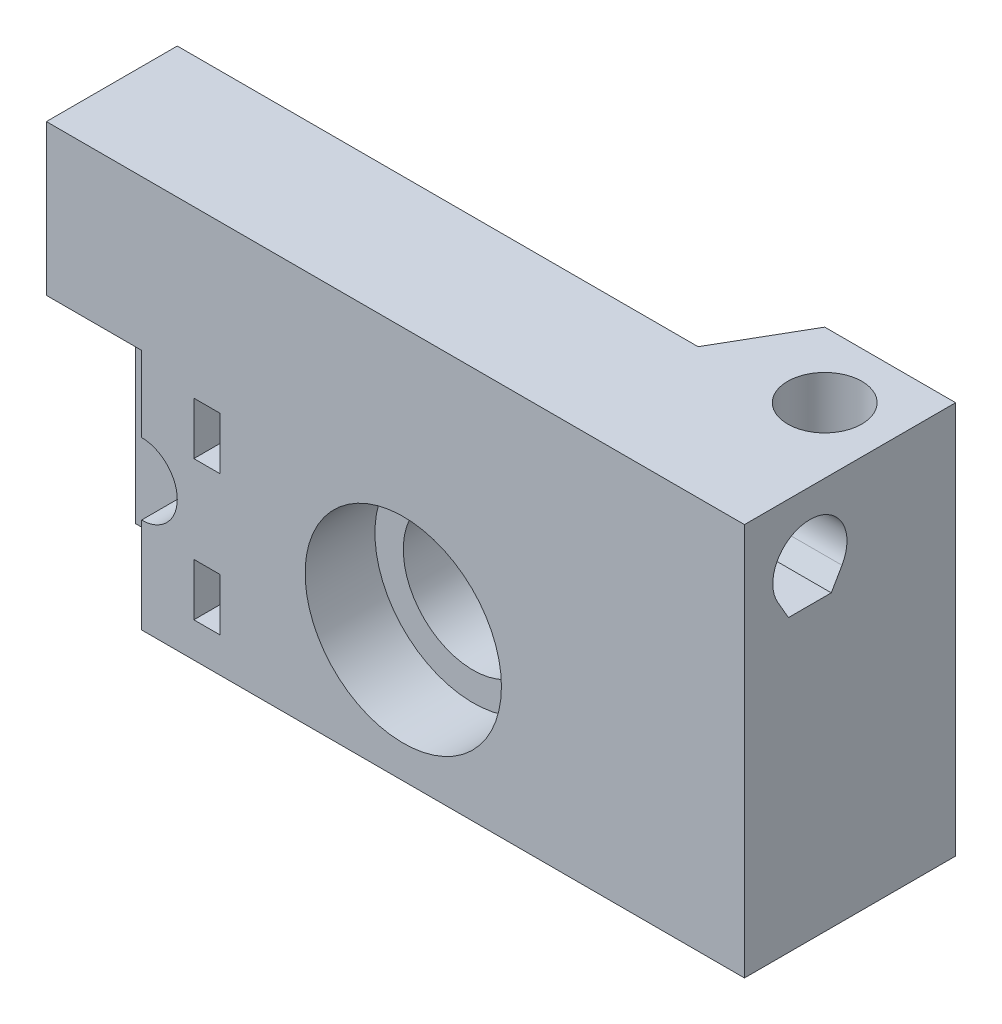
SolidWorks part; units mm, degrees
ref_plane "Piano frontale" through (0, 0, 0) normal (0, 0, 1) x (1, 0, 0)
ref_plane "Piano superiore" through (0, 0, 0) normal (0, 1, 0) x (1, 0, 0)
ref_plane "Piano destro" through (0, 0, 0) normal (1, 0, 0) x (0, 0, -1)
sketch "Schizzo2" plane through (0, 0, 0) normal (0, 0, 1) x (1, 0, 0)
  line L1 (40, -15) -> (-40, -15)
  line L2 (40, -15) -> (40, 15)
  line L3 (40, 15) -> (-40, 15)
  line L4 (-40, -15) -> (-40, 15)
  line L5 (40, -15) -> (-40, 15) construction
  line L6 (40, 15) -> (-40, -15) construction
  point P0 (0, 0)
  dimension "D1" = 30
  dimension "D2" = 80
extrude "Estrusione-Estrusione1" add sketch "Schizzo2" along normal mid plane 24.2
sketch "Schizzo3" plane through (0, -15, 0) normal (0, -1, 0) x (1, 0, 0)
  line L1 (40, 12.1) -> (40, -12.1) construction
  line L2 (-40, -12.1) -> (40, -12.1) construction
  circle A0 centre (32.5, -4.6) radius 4.25
  dimension "D2" = 8.5
  dimension "D1" = 7.5
  dimension "D3" = 7.5
extrude "Taglio-Estrusione1" cut sketch "Schizzo3" against normal through all contours A0
sketch "Schizzo4" plane through (0, 0, 12.1) normal (0, 0, 1) x (1, 0, 0)
  line L0 (0, 0) -> (0.9, 0) construction
  line L1 (28.25, -15) -> (36.75, -15) construction
  line L2 (28.25, -15) -> (36.75, -15) construction
  line L3 (32.5, -15) -> (32.5, 15) construction
  line L4 (40, 15) -> (-40, 15) construction
  circle A0 centre (0.9, 0) radius 11.25
  dimension "D1" = 22.5
  dimension "D2" = 31.6
extrude "Taglio-Estrusione2" cut sketch "Schizzo4" against normal blind 8
sketch "Schizzo5" plane through (0, 0, 4.1) normal (0, 0, 1) x (1, 0, 0)
  circle A0 centre (0.9, 0) radius 11.25 construction
  circle A1 centre (0.9, 0) radius 11.25 construction
  circle A2 centre (0.9, 0) radius 8
  dimension "D1" = 16
extrude "Taglio-Estrusione3" cut sketch "Schizzo5" against normal through all contours A2
sketch "Schizzo6" plane through (0, 15, 0) normal (0, 1, 0) x (1, 0, 0)
  line L4 (40, 12.1) -> (-40, 12.1)
  line L5 (-40, 12.1) -> (-40, -12.1)
  line L6 (-40, -12.1) -> (40, -12.1)
  line L7 (40, -12.1) -> (40, 12.1)
  line L8 (40, 12.1) -> (-40, 12.1)
  line L9 (-40, 12.1) -> (-40, -12.1)
  line L10 (-40, -12.1) -> (40, -12.1)
  line L11 (40, -12.1) -> (40, 12.1)
  circle A0 centre (32.5, 4.6) radius 4.25 construction
  circle A1 centre (32.5, 4.6) radius 4.25
  dimension "D1" = 0
extrude "Estrusione-Estrusione2" add sketch "Schizzo6" along normal blind 15
sketch "Schizzo7" plane through (40, 0, 0) normal (1, 0, 0) x (0, 0, -1)
  line L0 (-2.1463, 18.25) -> (-7.0537, 18.25)
  line L1 (-7.0537, 18.25) -> (-8.2806, 20.375)
  line L2 (-12.1, 30) -> (12.1, 30) construction
  line L3 (-2.1463, 18.25) -> (-0.9194, 20.375)
  line L4 (-12.1, -15) -> (-12.1, 30) construction
  arc A0 (-0.9194, 20.375) -> (-8.2806, 20.375) centre (-4.6, 22.5) ccw
  point P9 (-4.6, 18.25)
  dimension "D2" = 8.5
  dimension "D1" = 7.5
  dimension "D3" = 7.5
  dimension "D4" = 120
extrude "Taglio-Estrusione4" cut sketch "Schizzo7" against normal through all
sketch "Schizzo8" plane through (0, 0, 12.1) normal (0, 0, 1) x (1, 0, 0)
  line L0 (-29.1, 0) -> (0.9, 0) construction
  circle A0 centre (0.9, 0) radius 11.25 construction
  circle A1 centre (0.9, 0) radius 11.25 construction
  circle A2 centre (-29.1, 0) radius 4.1
  dimension "D2" = 8.2
  dimension "D1" = 30
sketch "Schizzo9" plane through (0, -15, 0) normal (0, -1, 0) x (1, 0, 0)
  line L0 (25, -12.1) -> (19.6884, -2.9)
  line L1 (-40, -12.1) -> (40, -12.1) construction
  line L2 (19.6884, -2.9) -> (-40, -2.9)
  line L3 (-40, 12.1) -> (-40, -12.1) construction
  line L4 (-40, -2.9) -> (-40, -12.1)
  line L5 (-40, -12.1) -> (25, -12.1)
  line L6 (-40, 12.1) -> (40, 12.1) construction
  dimension "D1" = 15
  dimension "D2" = 60
  dimension "D3" = 15
extrude "Taglio-Estrusione5" cut sketch "Schizzo9" against normal through all
extrude "Taglio-Estrusione6" cut sketch "Schizzo8" against normal blind 12 contours A2
sketch "Schizzo10" plane through (-40, 0, 0) normal (-1, 0, 0) x (0, 0, 1)
  line L0 (1.9, 12.75) -> (1.9, -15)
  line L2 (1.9, 12.75) -> (12.1, 12.75)
  line L3 (12.1, 30) -> (12.1, -15) construction
  line L5 (12.1, -4.1) -> (12.1, 4.1) construction
  line L6 (12.1, -4.1) -> (12.1, 4.1) construction
  line L7 (12.1, 0) -> (1.9, 0) construction
  line L8 (12.1, -15) -> (-2.9, -15) construction
  line L9 (1.9, -15) -> (12.1, -15)
  line L10 (12.1, -15) -> (12.1, 12.75)
  point P15 (7.1, 0)
  dimension "D1" = 10.2
  dimension "D5" = 12.75
extrude "Taglio-Estrusione7" cut sketch "Schizzo10" against normal blind 10.9 contours L0 L9 L10 L2
sketch "Schizzo11" plane through (-29.1, 0, 0) normal (-1, 0, 0) x (0, 0, 1)
  line L0 (12.1, -4.1) -> (12.1, 4.1) construction
  line L1 (12.1, -4.1) -> (12.1, 4.1) construction
  line L2 (12.1, 0) -> (7.1, 0) construction
  line L3 (7.1, -8) -> (7.1, 8) construction
  line L4 (8.1104, 6.25) -> (6.0896, 6.25)
  line L5 (8.1104, -9.75) -> (6.0896, -9.75)
  line L6 (8.1104, -9.75) -> (8.6155, -8.875)
  line L7 (6.0896, -9.75) -> (5.5845, -8.875)
  line L8 (8.1104, 6.25) -> (8.6155, 7.125)
  line L9 (6.0896, 6.25) -> (5.5845, 7.125)
  arc A0 (8.6155, 7.125) -> (5.5845, 7.125) centre (7.1, 8) ccw
  arc A1 (8.6155, -8.875) -> (5.5845, -8.875) centre (7.1, -8) ccw
  point P8 (7.1, 0)
  point P13 (7.1, 6.25)
  point P16 (7.1, -9.75)
  dimension "D3" = 3.5
  dimension "D1" = 5
  dimension "D2" = 8
  dimension "D4" = 120
  dimension "D5" = 120
extrude "Taglio-Estrusione8" cut sketch "Schizzo11" against normal blind 12
sketch "Schizzo12" plane through (0, 0, 12.1) normal (0, 0, 1) x (1, 0, 0)
  line L0 (-21.6, -8) -> (-21.6, 8) construction
  line L1 (-23.1, -11) -> (-20.1, -11)
  line L2 (-23.1, -11) -> (-23.1, -5)
  line L3 (-23.1, -5) -> (-20.1, -5)
  line L4 (-20.1, -11) -> (-20.1, -5)
  line L5 (-23.1, -11) -> (-20.1, -5) construction
  line L6 (-23.1, -5) -> (-20.1, -11) construction
  line L7 (-23.1, 5) -> (-20.1, 5)
  line L8 (-23.1, 5) -> (-23.1, 11)
  line L9 (-23.1, 11) -> (-20.1, 11)
  line L10 (-20.1, 5) -> (-20.1, 11)
  line L11 (-23.1, 5) -> (-20.1, 11) construction
  line L12 (-23.1, 11) -> (-20.1, 5) construction
  line L13 (-29.1, 0) -> (-21.6, 0) construction
  arc A1 (-29.1, -4.1) -> (-29.1, 4.1) centre (-29.1, 0) ccw construction
  arc A2 (-29.1, -4.1) -> (-29.1, 4.1) centre (-29.1, 0) ccw construction
  point P3 (-21.6, -8)
  point P8 (-21.6, 8)
  dimension "D1" = 8
  dimension "D2" = 6
  dimension "D3" = 3
  dimension "D4" = 7.5
extrude "Taglio-Estrusione9" cut sketch "Schizzo12" against normal blind 8.2
